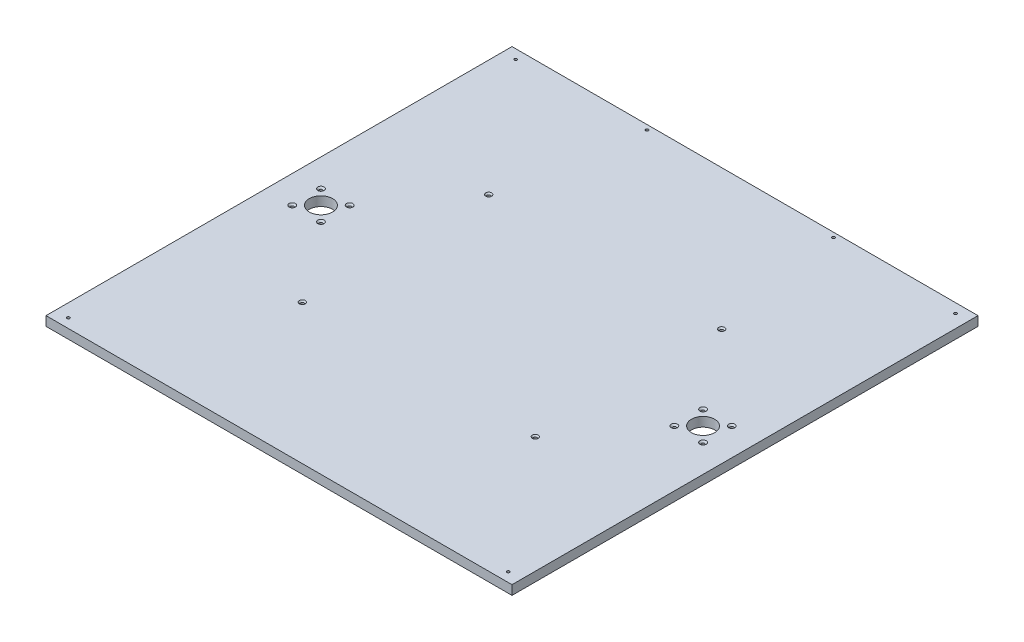
SolidWorks part; units mm, degrees
material "Buk"
ref_plane "Płaszczyzna przednia" through (0, 0, 0) normal (0, 0, 1) x (1, 0, 0)
ref_plane "Płaszczyzna górna" through (0, 0, 0) normal (0, 1, 0) x (1, 0, 0)
ref_plane "Płaszczyzna prawa" through (0, 0, 0) normal (1, 0, 0) x (0, 0, -1)
sketch "Szkic1" plane through (0, 0, 0) normal (0, 1, 0) x (1, 0, 0)
  line L1 (0, 0) -> (500, 0)
  line L2 (0, 0) -> (0, 500)
  line L3 (0, 500) -> (500, 500)
  line L4 (500, 0) -> (500, 500)
  dimension "D1" = 500
  dimension "D2" = 500
extrude "Dodanie-wyciągnięcie1" add sketch "Szkic1" along normal blind 10
sketch "Szkic2" plane through (0, 10, 0) normal (0, 1, 0) x (1, 0, 0)
  line L0 (0, 500) -> (0, 0) construction
  line L1 (500, 500) -> (0, 500) construction
  line L3 (500, 0) -> (500, 500) construction
  circle A0 centre (45, 250) radius 12.5
  circle A1 centre (455, 250) radius 12.5
  dimension "D1" = 25
  dimension "D2" = 45
  dimension "D3" = 250
  dimension "D4" = 25
  dimension "D5" = 45
extrude "Wytnij-wyciągnięcie1" cut sketch "Szkic2" against normal through all
sketch "Szkic5" plane through (0, 10, 0) normal (0, 1, 0) x (1, 0, 0)
  line L0 (0, 500) -> (0, 0) construction
  line L1 (0, 0) -> (500, 0) construction
  circle A0 centre (125, 150) radius 1.6
  circle A1 centre (375, 150) radius 1.6
  circle A2 centre (375, 350) radius 1.6
  circle A3 centre (125, 350) radius 1.6
  dimension "D1" = 3.2
  dimension "D2" = 125
  dimension "D3" = 150
  dimension "D4" = 2
  dimension "D5" = 2
hole_wizard "Pogłębienie stożkowe pod M3 Wkręt ustalający1" positions "Szkic6" profile "Szkic7" countersink size "M3" standard "Ansi Metric" end condition through all
sketch "Szkic6" plane through (0, 10, 0) normal (0, 1, 0) x (1, 0, 0)
  point P0 (439.6, 265.4)
  point P3 (439.6, 234.6)
  point P6 (470.4, 234.6)
  point P9 (470.4, 265.4)
  point P12 (60.4, 234.6)
  point P15 (60.4, 265.4)
  point P18 (29.6, 234.6)
  point P21 (29.6, 265.4)
sketch "Szkic7" plane through (439.6, 10, -265.4) normal (1, 0, 0) x (0, 0, 1)
  line L0 (0, 0) -> (0, 10)
  line L1 (0, 10) -> (1.7, 10)
  line L2 (1.7, 10) -> (1.7, 1.66)
  line L3 (1.7, 1.66) -> (3.36, 0)
  line L5 (3.36, 0) -> (0, 0)
  line L6 (-1.7, 1.66) -> (-3.36, 0) construction
  line L11 (0, -6.35) -> (0, 107.95) construction
  dimension "Œrednica otworu na wylot" = 3.4
  dimension "G³êbokoœæ otworu na wylot" = 10
  dimension "Œrednica zewnêtrznego pog³êbienia sto¿kowego" = 6.72
  dimension "K¹t zewnêtrznego pog³êbienia sto¿kowego" = 90
hole_wizard "Pogłębienie stożkowe pod M3 wkręt do części metalowych z łbem soczewkowym1" positions "Szkic8" profile "Szkic9" countersink size "M3" standard "Ansi Metric"
sketch "Szkic8" plane through (0, 10, 0) normal (0, 1, 0) x (1, 0, 0)
  point P0 (375, 350)
  point P3 (375, 150)
  point P6 (125, 350)
  point P9 (125, 150)
sketch "Szkic9" plane through (375, 10, -350) normal (1, 0, 0) x (0, 0, 1)
  line L0 (0, 0) -> (0, 11.0215)
  line L1 (0, 11.0215) -> (1.7, 10)
  line L2 (1.7, 10) -> (1.7, 1.45)
  line L3 (1.7, 1.45) -> (3.15, 0)
  line L5 (3.15, 0) -> (0, 0)
  line L6 (-1.7, 1.45) -> (-3.15, 0) construction
  line L10 (0, 11.0215) -> (-1.7, 10) construction
  line L11 (0, -6.35) -> (0, 107.95) construction
  dimension "Œrednica otworu" = 3.4
  dimension "G³êbokoœc otworu" = 10
  dimension "Œrednica zewnêtrznego pog³êbienia sto¿kowego" = 6.3
  dimension "K¹t zewnêtrznego pog³êbienia sto¿kowego" = 90
  dimension "K¹t wiert³a" = 118
hole_wizard "Otwory ustalające Ø3.0mm1" positions "Szkic10" profile "Szkic11" hole size "Ø3.0" standard "Ansi Metric"
sketch "Szkic10" plane through (0, 0, 0) normal (0, -1, 0) x (-1, 0, 0)
  line L0 (-10, 0) -> (-10, 500) construction
  line L2 (-500, 500) -> (0, 500) construction
  line L3 (-490, 500) -> (-490, 0) construction
  line L4 (0, 0) -> (-500, 0) construction
  point P0 (-486, 490)
  point P2 (-486, 10)
  point P4 (-14, 10)
  point P6 (-14, 490)
  dimension "D1" = 4
  dimension "D2" = 10
  dimension "D3" = 4
  dimension "D4" = 10
  dimension "D5" = 4
  dimension "D6" = 10
  dimension "D7" = 4
  dimension "D8" = 10
sketch "Szkic11" plane through (486, 0, -490) normal (1, 0, 0) x (0, 0, -1)
  line L0 (0, 0) -> (0, 10.9013)
  line L1 (0, 10.9013) -> (1.5, 10)
  line L2 (1.5, 10) -> (1.5, 0)
  line L5 (1.5, 0) -> (0, 0)
  line L10 (0, 10.9013) -> (-1.5, 10) construction
  line L11 (0, -6.35) -> (0, 107.95) construction
  dimension "Œrednica otworu" = 3
  dimension "G³êbokoœæ otworu" = 10
  dimension "K¹t wiert³a" = 118
hole_wizard "Otwory ustalające Ø3.0mm2" positions "Szkic12" profile "Szkic13" hole size "Ø3.0" standard "Ansi Metric"
sketch "Szkic12" plane through (0, 0, 0) normal (0, -1, 0) x (-1, 0, 0)
  line L0 (-500, 500) -> (0, 500) construction
  line L1 (0, 500) -> (0, 0) construction
  line L2 (-500, 0) -> (-500, 500) construction
  point P0 (-150, 495)
  point P2 (-350, 495)
  dimension "D1" = 5
  dimension "D2" = 150
  dimension "D3" = 5
  dimension "D4" = 150
sketch "Szkic13" plane through (150, 0, -495) normal (1, 0, 0) x (0, 0, -1)
  line L0 (0, 0) -> (0, 10.9013)
  line L1 (0, 10.9013) -> (1.5, 10)
  line L2 (1.5, 10) -> (1.5, 0)
  line L5 (1.5, 0) -> (0, 0)
  line L10 (0, 10.9013) -> (-1.5, 10) construction
  line L11 (0, -6.35) -> (0, 107.95) construction
  dimension "Œrednica otworu" = 3
  dimension "G³êbokoœæ otworu" = 10
  dimension "K¹t wiert³a" = 118
